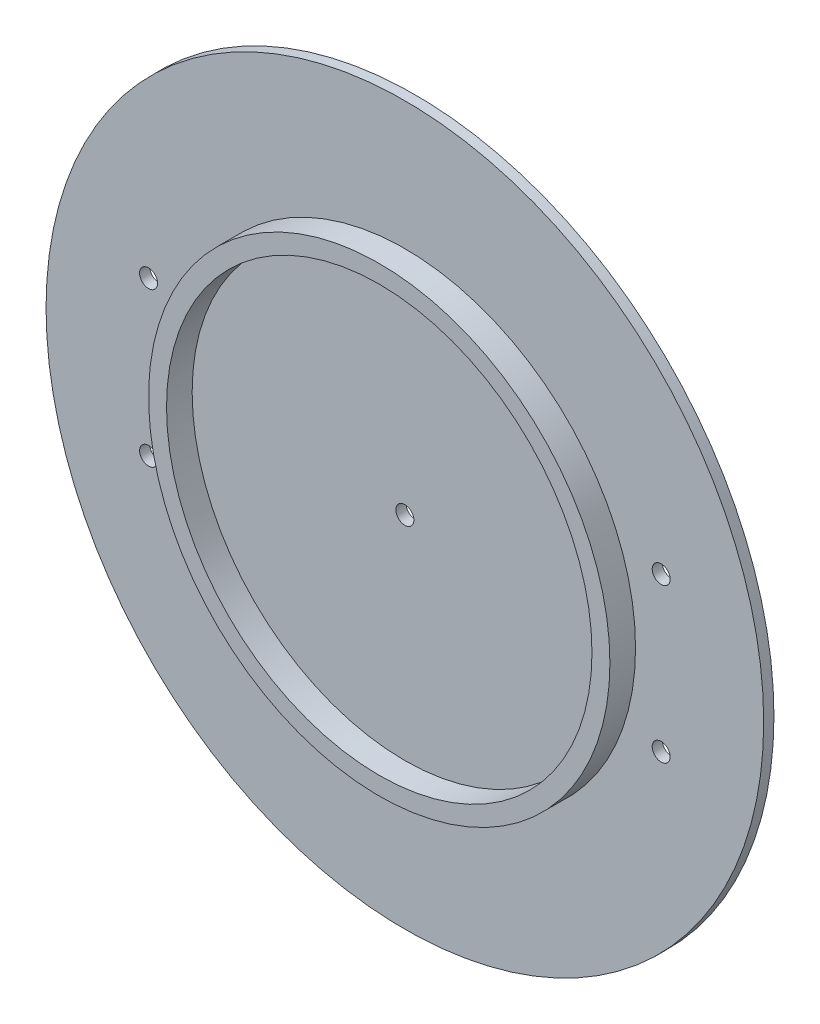
SolidWorks part; units mm, degrees
ref_plane "Front Plane" through (0, 0, 0) normal (0, 0, 1) x (1, 0, 0)
ref_plane "Top Plane" through (0, 0, 0) normal (0, 1, 0) x (1, 0, 0)
ref_plane "Right Plane" through (0, 0, 0) normal (1, 0, 0) x (0, 0, -1)
sketch "Sketch1" plane through (0, 0, 0) normal (0, 0, 1) x (1, 0, 0)
  circle A0 centre (0, 0) radius 70
  dimension "D1" = 140
extrude "Boss-Extrude1" add sketch "Sketch1" along normal blind 2
sketch "Sketch2" plane through (0, 0, 2) normal (0, 0, 1) x (1, 0, 0)
  line L1 (-50, 15) -> (50, 15) construction
  line L2 (-50, 15) -> (-50, -15) construction
  line L3 (-50, -15) -> (50, -15) construction
  line L4 (50, 15) -> (50, -15) construction
  line L5 (-50, 15) -> (50, -15) construction
  line L6 (-50, -15) -> (50, 15) construction
  circle A0 centre (-50, 15) radius 1.75
  circle A1 centre (50, 15) radius 1.75
  circle A2 centre (50, -15) radius 1.75
  circle A3 centre (-50, -15) radius 1.75
  circle A4 centre (0, 0) radius 1.75
  point P0 (0, 0)
  dimension "D1" = 3.5
  dimension "D2" = 100
  dimension "D3" = 30
extrude "Cut-Extrude1" cut sketch "Sketch2" against normal through all
sketch "Sketch4" plane through (0, 0, 2) normal (0, 0, 1) x (1, 0, 0)
  circle A0 centre (0, 0) radius 41.5
  circle A1 centre (0, 0) radius 45
  dimension "D1" = 83
  dimension "D2" = 90
extrude "Boss-Extrude2" add sketch "Sketch4" along normal blind 5
